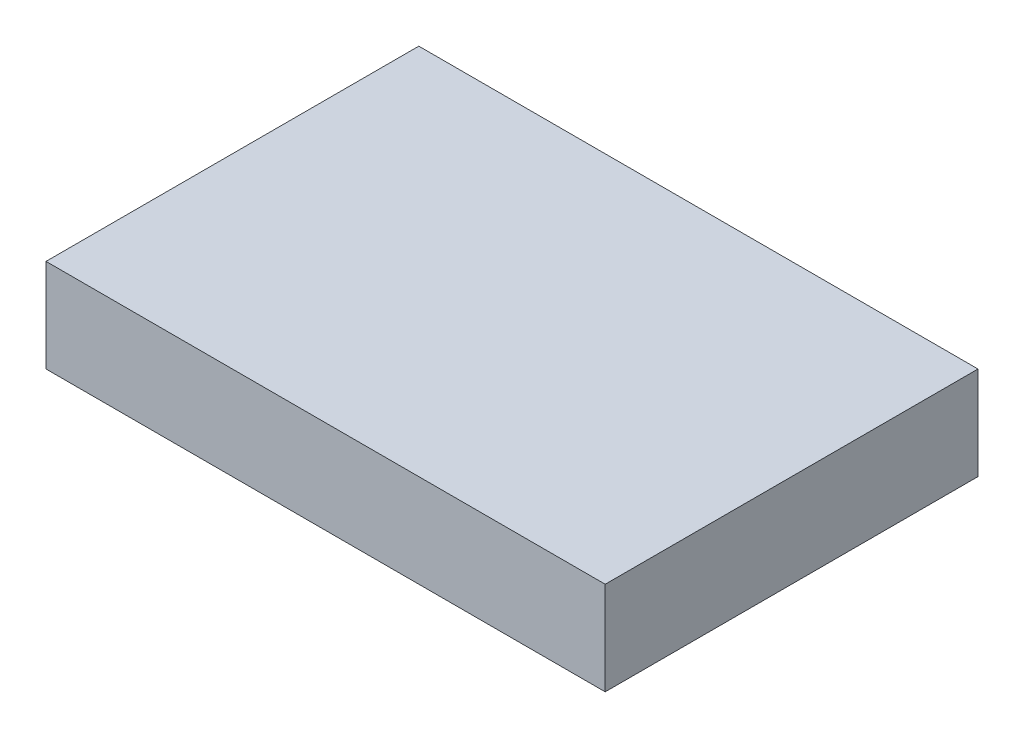
SolidWorks part; units mm, degrees
ref_plane "Front Plane" through (0, 0, 0) normal (0, 0, 1) x (1, 0, 0)
ref_plane "Top Plane" through (0, 0, 0) normal (0, 1, 0) x (1, 0, 0)
ref_plane "Right Plane" through (0, 0, 0) normal (1, 0, 0) x (0, 0, -1)
sketch "Sketch1" plane through (0, 0, 0) normal (0, 1, 0) x (1, 0, 0)
  line L1 (-15, -10) -> (15, -10)
  line L2 (-15, -10) -> (-15, 10)
  line L3 (-15, 10) -> (15, 10)
  line L4 (15, -10) -> (15, 10)
  line L5 (-15, -10) -> (15, 10) construction
  line L6 (-15, 10) -> (15, -10) construction
  point P0 (0, 0)
  dimension "D1" = 20
  dimension "D2" = 30
extrude "Boss-Extrude1" add sketch "Sketch1" along normal blind 5
